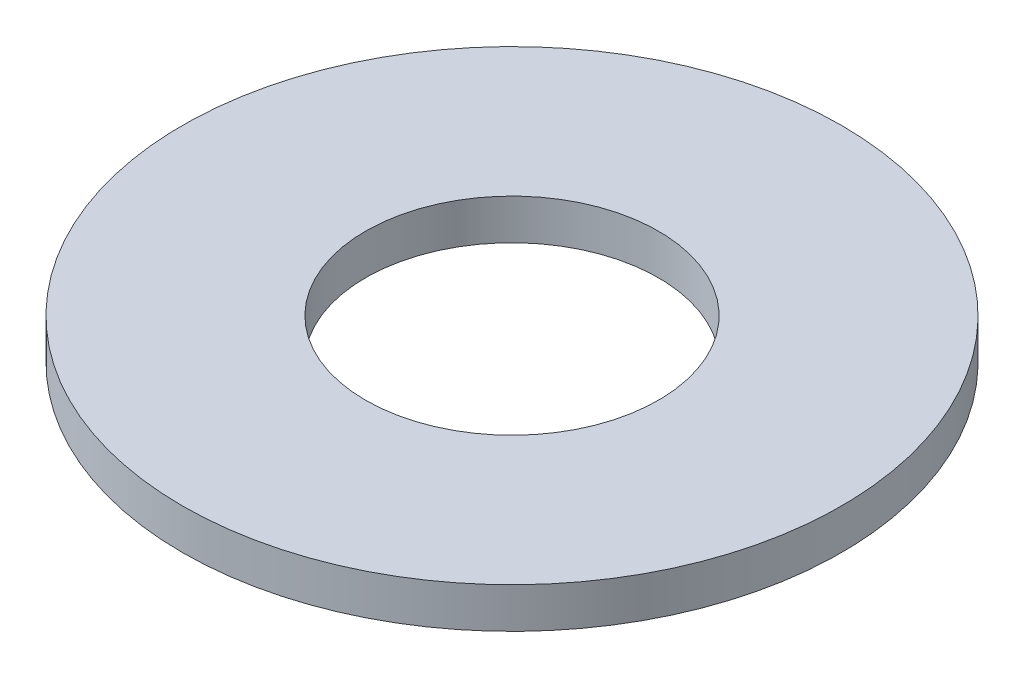
SolidWorks part; units mm, degrees
ref_plane "Front Plane" through (0, 0, 0) normal (0, 0, 1) x (1, 0, 0)
ref_plane "Top Plane" through (0, 0, 0) normal (0, 1, 0) x (1, 0, 0)
ref_plane "Right Plane" through (0, 0, 0) normal (1, 0, 0) x (0, 0, -1)
sketch "Sketch1" plane through (0, 0, 0) normal (0, 1, 0) x (1, 0, 0)
  circle A0 centre (0, 0) radius 14.2875
  dimension "OD" = 28.575
extrude "Boss-Extrude1" add sketch "Sketch1" along normal blind 1.7526
sketch "Sketch5" plane through (0, 1.7526, 0) normal (0, 1, 0) x (-1, 0, 0)
  circle A0 centre (0, 0) radius 6.35
  dimension "ID" = 12.7
extrude "Cut-Extrude1" cut sketch "Sketch5" against normal through all
